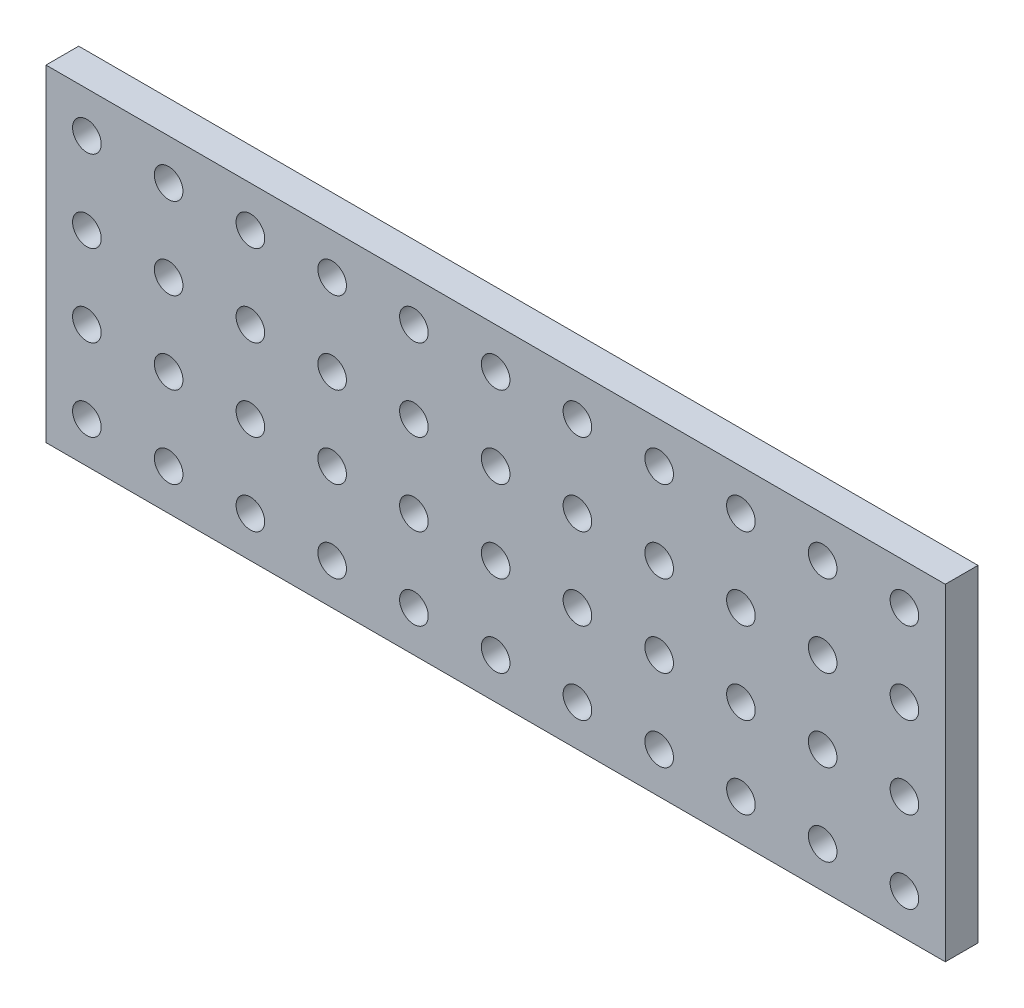
SolidWorks part; units mm, degrees
ref_plane "Plan de face" through (0, 0, 0) normal (0, 0, 1) x (1, 0, 0)
ref_plane "Plan de dessus" through (0, 0, 0) normal (0, 1, 0) x (1, 0, 0)
ref_plane "Plan de droite" through (0, 0, 0) normal (1, 0, 0) x (0, 0, -1)
sketch "Esquisse1" plane through (0, 0, 0) normal (0, 0, 1) x (1, 0, 0)
  line L1 (0, 0) -> (110, 0)
  line L2 (0, 0) -> (0, -40)
  line L3 (0, -40) -> (110, -40)
  line L4 (110, 0) -> (110, -40)
  circle A0 centre (5, -5) radius 1.75
  circle A1 centre (15, -5) radius 1.75
  circle A2 centre (25, -5) radius 1.75
  circle A3 centre (35, -5) radius 1.75
  circle A4 centre (45, -5) radius 1.75
  circle A5 centre (55, -5) radius 1.75
  circle A6 centre (65, -5) radius 1.75
  circle A7 centre (75, -5) radius 1.75
  circle A8 centre (85, -5) radius 1.75
  circle A9 centre (95, -5) radius 1.75
  circle A10 centre (105, -5) radius 1.75
  circle A11 centre (15, -15) radius 1.75
  circle A12 centre (25, -15) radius 1.75
  circle A13 centre (35, -15) radius 1.75
  circle A14 centre (45, -15) radius 1.75
  circle A15 centre (55, -15) radius 1.75
  circle A16 centre (65, -15) radius 1.75
  circle A17 centre (75, -15) radius 1.75
  circle A18 centre (85, -15) radius 1.75
  circle A19 centre (95, -15) radius 1.75
  circle A20 centre (105, -15) radius 1.75
  circle A21 centre (15, -25) radius 1.75
  circle A22 centre (25, -25) radius 1.75
  circle A23 centre (35, -25) radius 1.75
  circle A24 centre (45, -25) radius 1.75
  circle A25 centre (55, -25) radius 1.75
  circle A26 centre (65, -25) radius 1.75
  circle A27 centre (75, -25) radius 1.75
  circle A28 centre (85, -25) radius 1.75
  circle A29 centre (95, -25) radius 1.75
  circle A30 centre (105, -25) radius 1.75
  circle A31 centre (15, -35) radius 1.75
  circle A32 centre (25, -35) radius 1.75
  circle A33 centre (35, -35) radius 1.75
  circle A34 centre (45, -35) radius 1.75
  circle A35 centre (55, -35) radius 1.75
  circle A36 centre (65, -35) radius 1.75
  circle A37 centre (75, -35) radius 1.75
  circle A38 centre (85, -35) radius 1.75
  circle A39 centre (95, -35) radius 1.75
  circle A40 centre (105, -35) radius 1.75
  circle A41 centre (5, -15) radius 1.75
  circle A42 centre (5, -25) radius 1.75
  circle A43 centre (5, -35) radius 1.75
  dimension "D5" = 3.5
  dimension "D1" = 110
  dimension "D2" = 40
  dimension "D3" = 5
  dimension "D4" = 5
  dimension "D6" = 11
  dimension "D7" = 4
extrude "Boss.-Extru.1" add sketch "Esquisse1" along normal blind 4
